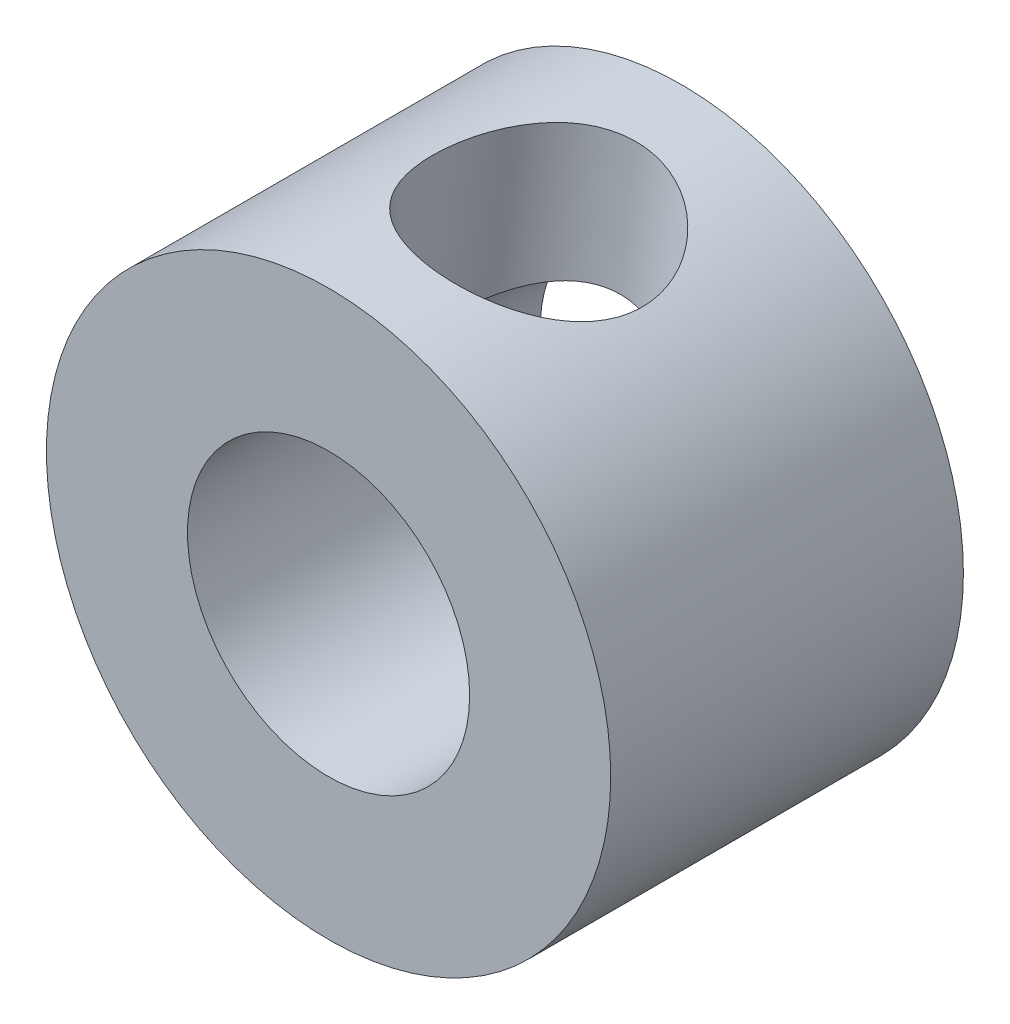
SolidWorks part; units mm, degrees
material "AISI 1020"
ref_plane "正面" through (0, 0, 0) normal (0, 0, 1) x (1, 0, 0)
ref_plane "平面" through (0, 0, 0) normal (0, 1, 0) x (1, 0, 0)
ref_plane "右側面" through (0, 0, 0) normal (1, 0, 0) x (0, 0, -1)
sketch "ｽｹｯﾁ1" plane through (0, 0, 0) normal (0, 0, 1) x (1, 0, 0)
  circle A0 centre (0, 0) radius 4
  dimension "D1" = 8
extrude "ﾎﾞｽ - 押し出し1" add sketch "ｽｹｯﾁ1" along normal blind 5
sketch "ｽｹｯﾁ2" plane through (0, 0, 5) normal (0, 0, 1) x (1, 0, 0)
  circle A0 centre (0, 0) radius 2
  dimension "D1" = 4
extrude "ｶｯﾄ - 押し出し1" cut sketch "ｽｹｯﾁ2" against normal through all
hole_wizard "M3x0.5 ねじ穴1" positions "3Dｽｹｯﾁ1" profile "ｽｹｯﾁ3" tap size "M3x0.5" standard "JIS"
sketch3d "3Dｽｹｯﾁ1"
  point P0 (0.4973, 3.969, 2.5)
  dimension "D1" = 2.5
sketch "ｽｹｯﾁ3" plane through (0.4973, 3.969, 2.5) normal (0, 0, 1) x (-0.9922, 0.1243, 0)
  line L0 (0, 0) -> (0, 2)
  line L1 (0, 2) -> (1.5, 2)
  line L2 (1.5, 2) -> (1.5, 0)
  line L5 (1.5, 0) -> (0, 0)
  line L11 (0, -6.35) -> (0, 107.95) construction
  dimension "ねじ山の主要直径" = 3
  dimension "次ｻｰﾌｪｽまでのねじ下穴ﾄﾞﾘﾙの深さ" = 2
